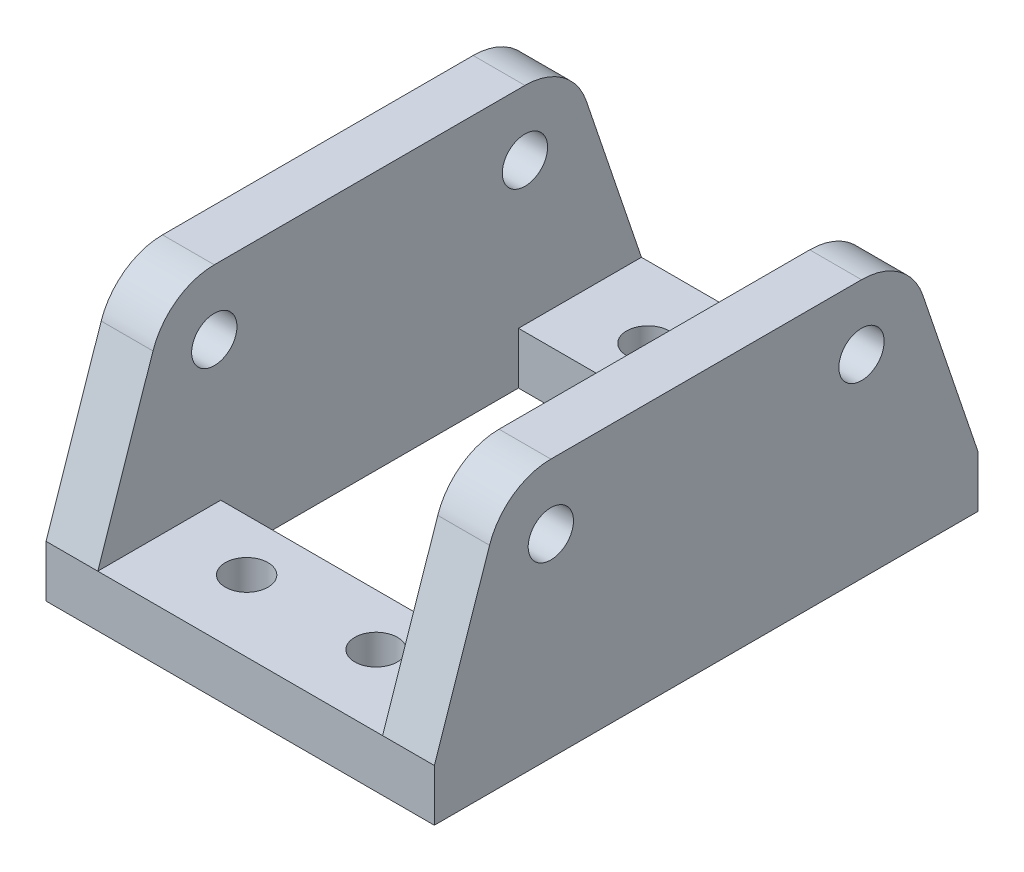
SolidWorks part; units mm, degrees
material "ABS"
ref_plane "Plano frontal" through (0, 0, 0) normal (0, 0, 1) x (1, 0, 0)
ref_plane "Plano superior" through (0, 0, 0) normal (0, 1, 0) x (1, 0, 0)
ref_plane "Plano direito" through (0, 0, 0) normal (1, 0, 0) x (0, 0, -1)
sketch "Esboço1" plane through (0, 0, 0) normal (0, 1, 0) x (1, 0, 0)
  line L0 (-15, 25) -> (15, 25)
  line L1 (-11, 21) -> (11, 21)
  line L2 (-11, 21) -> (-11, -21)
  line L3 (-11, -21) -> (11, -21)
  line L4 (11, 21) -> (11, -21)
  line L5 (-11, 21) -> (11, -21) construction
  line L6 (-11, -21) -> (11, 21) construction
  line L7 (15, 25) -> (15, -25)
  line L8 (-15, -25) -> (15, -25)
  line L9 (-15, 25) -> (-15, -25)
  line L10 (-4, 7) -> (4, 7) construction
  line L11 (4, 7) -> (4, 17) construction
  line L12 (4, 17) -> (-4, 17) construction
  line L13 (-4, 17) -> (-4, 7) construction
  line L14 (-11, 0) -> (11, 0) construction
  line L15 (-4, -17) -> (-4, -7) construction
  line L16 (4, -17) -> (-4, -17) construction
  line L17 (4, -7) -> (4, -17) construction
  line L18 (-4, -7) -> (4, -7) construction
  point P0 (0, 0)
  point P12 (0, 7)
  dimension "D2" = 30
  dimension "D3" = 10
  dimension "D4" = 8
  dimension "D5" = 50
  dimension "D6" = 14
  dimension "D1" = 4
extrude "Ressalto-extrusão1" add sketch "Esboço1" along normal blind 20
sketch "Esboço3" plane through (15, 0, 0) normal (1, 0, 0) x (0, 0, -1)
  line L0 (0, 0) -> (0, 23.3091) construction
  line L1 (-25, 0) -> (25, 0) construction
  line L2 (-12, 15) -> (12, 15) construction
  line L3 (-25, 20) -> (25, 20) construction
  circle A0 centre (-12, 15) radius 1.75
  circle A1 centre (12, 15) radius 1.75
  circle A2 centre (-12, 15) radius 5 construction
  circle A3 centre (12, 15) radius 5 construction
  point P8 (0, 15)
  dimension "D1" = 10
  dimension "D2" = 3.5
  dimension "D3" = 14
  dimension "D4" = 5
extrude "Corte-extrusão2" cut sketch "Esboço3" against normal through all
sketch "Esboço4" plane through (0, 0, 0) normal (0, 1, 0) x (1, 0, 0)
  line L0 (0, 21) -> (0, -21) construction
  line L2 (-11, 11.5) -> (11, 11.5)
  line L4 (-11, 0) -> (11, 0) construction
  line L5 (-11, 21) -> (-11, -21) construction
  line L6 (-11, 11.5) -> (-11, 21)
  line L7 (11, -21) -> (11, 21) construction
  line L8 (-11, 21) -> (11, 21)
  line L9 (-11, -21) -> (11, -21)
  line L10 (-11, -11.5) -> (-11, -21)
  line L11 (-11, -11.5) -> (11, -11.5)
  line L12 (11, -11.5) -> (11, -21)
  line L13 (11, 11.5) -> (11, 21)
  circle A0 centre (5, -15.5) radius 1.65
  circle A1 centre (-5, 15.5) radius 1.65
  circle A2 centre (-5, -15.5) radius 1.65
  circle A3 centre (5, 15.5) radius 1.65
  point P28 (0, -11.5)
  point P31 (0, 11.5)
  dimension "D1" = 31
  dimension "D2" = 3.3
  dimension "D3" = 23
  dimension "D4" = 10
extrude "Ressalto-extrusão2" add sketch "Esboço4" along normal blind 4
sketch "Esboço5" plane through (-15, 0, 0) normal (-1, 0, 0) x (0, 0, 1)
  line L0 (-16.7363, 16.6024) -> (-21, 4)
  line L2 (-25, 0) -> (25, 0) construction
  line L3 (25, 0) -> (25, 4)
  line L4 (0, 0) -> (0, 20) construction
  line L5 (-25, 20) -> (25, 20) construction
  line L6 (21, 0) -> (25, 0)
  line L7 (-25, 20) -> (-12, 20)
  line L8 (-25, 20) -> (-25, 4)
  line L9 (21, 4) -> (21, 0)
  line L10 (25, 20) -> (25, 4)
  line L11 (25, 20) -> (12, 20)
  line L12 (-21, 4) -> (-21, 0)
  line L13 (-21, 0) -> (-25, 0)
  line L14 (-25, 0) -> (-25, 4)
  line L15 (16.7363, 16.6024) -> (21, 4)
  arc A0 (-12, 20) -> (-16.7363, 16.6024) centre (-12, 15) ccw
  arc A1 (12, 20) -> (16.7363, 16.6024) centre (12, 15) cw
  dimension "D1" = 4
  dimension "D2" = 4
extrude "Corte-extrusão3" cut sketch "Esboço5" against normal through all both and the other way through all
